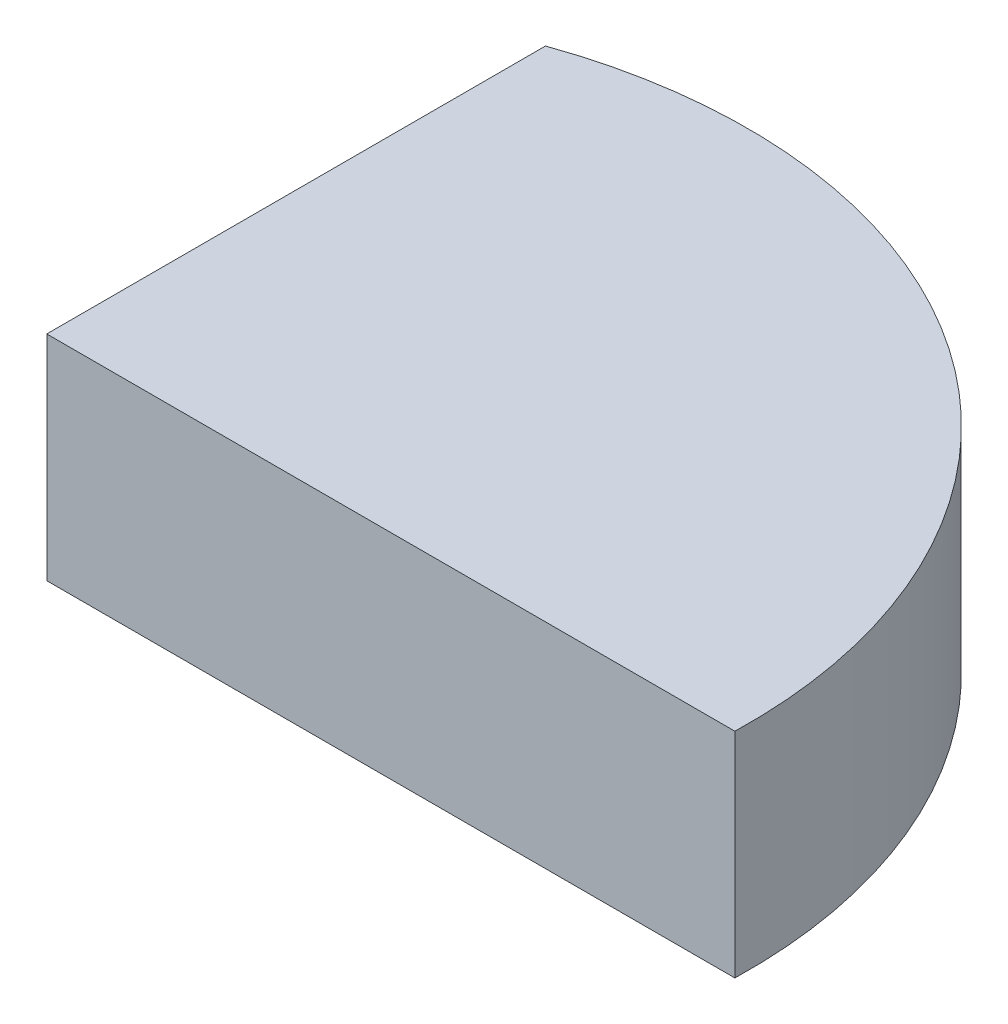
SolidWorks part; units mm, degrees
material "Plain Carbon Steel"
ref_plane "Front Plane" through (0, 0, 0) normal (0, 0, 1) x (1, 0, 0)
ref_plane "Top Plane" through (0, 0, 0) normal (0, 1, 0) x (1, 0, 0)
ref_plane "Right Plane" through (0, 0, 0) normal (1, 0, 0) x (0, 0, -1)
sketch "Sketch1" plane through (0, 0, 0) normal (0, 1, 0) x (1, 0, 0)
  line L0 (0, 0) -> (0, 44.45)
  line L2 (0, 0) -> (61.3329, 0)
  arc A1 (0, 44.45) -> (61.3329, 0) centre (15.3892, 1.1451) cw
  dimension "D1" = 44.45
extrude "Boss-Extrude1" add sketch "Sketch1" along normal blind 19.05
